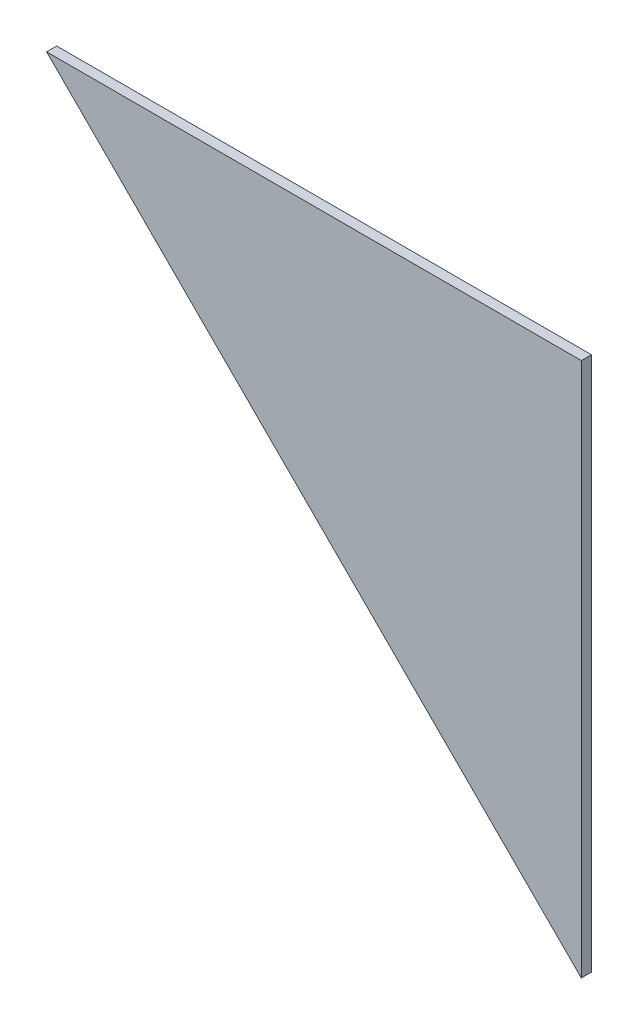
SolidWorks part; units mm, degrees
ref_plane "前基準面" through (0, 0, 0) normal (0, 0, 1) x (1, 0, 0)
ref_plane "上基準面" through (0, 0, 0) normal (0, 1, 0) x (1, 0, 0)
ref_plane "右基準面" through (0, 0, 0) normal (1, 0, 0) x (0, 0, -1)
sketch "草圖1" plane through (0, 0, 0) normal (0, 0, 1) x (1, 0, 0)
  line L0 (0, 0) -> (0, 106.066)
  line L1 (0, 106.066) -> (-106.066, 106.066)
  line L2 (-106.066, 106.066) -> (0, 0)
  dimension "D1" = 135
  dimension "D2" = 150
extrude "填料-伸長1" add sketch "草圖1" along normal blind 2
